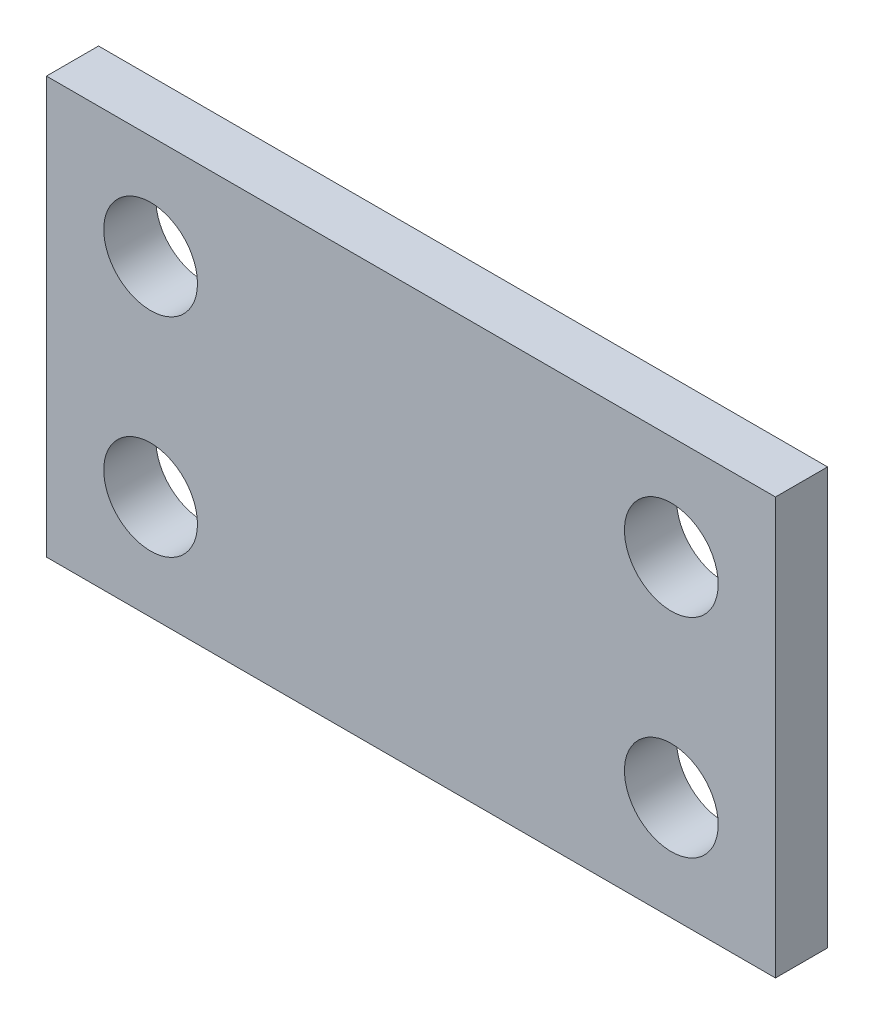
SolidWorks part; units mm, degrees
ref_plane "Płaszczyzna przednia" through (0, 0, 0) normal (0, 0, 1) x (1, 0, 0)
ref_plane "Płaszczyzna górna" through (0, 0, 0) normal (0, 1, 0) x (1, 0, 0)
ref_plane "Płaszczyzna prawa" through (0, 0, 0) normal (1, 0, 0) x (0, 0, -1)
sketch "Szkic1" plane through (0, 0, 0) normal (0, 0, 1) x (1, 0, 0)
  line L1 (-70, 40) -> (70, 40)
  line L2 (-70, 40) -> (-70, -40)
  line L3 (-70, -40) -> (70, -40)
  line L4 (70, 40) -> (70, -40)
  line L5 (-70, 40) -> (70, -40) construction
  line L6 (-70, -40) -> (70, 40) construction
  circle A0 centre (50, 20) radius 9
  circle A1 centre (-50, 20) radius 9
  circle A2 centre (-50, -20) radius 9
  circle A3 centre (50, -20) radius 9
  point P0 (0, 0)
  dimension "D7" = 18
  dimension "D1" = 140
  dimension "D2" = 80
  dimension "D3" = 20
  dimension "D4" = 20
  dimension "D5" = 2
  dimension "D6" = 2
extrude "Dodanie-wyciągnięcie1" add sketch "Szkic1" along normal blind 10
